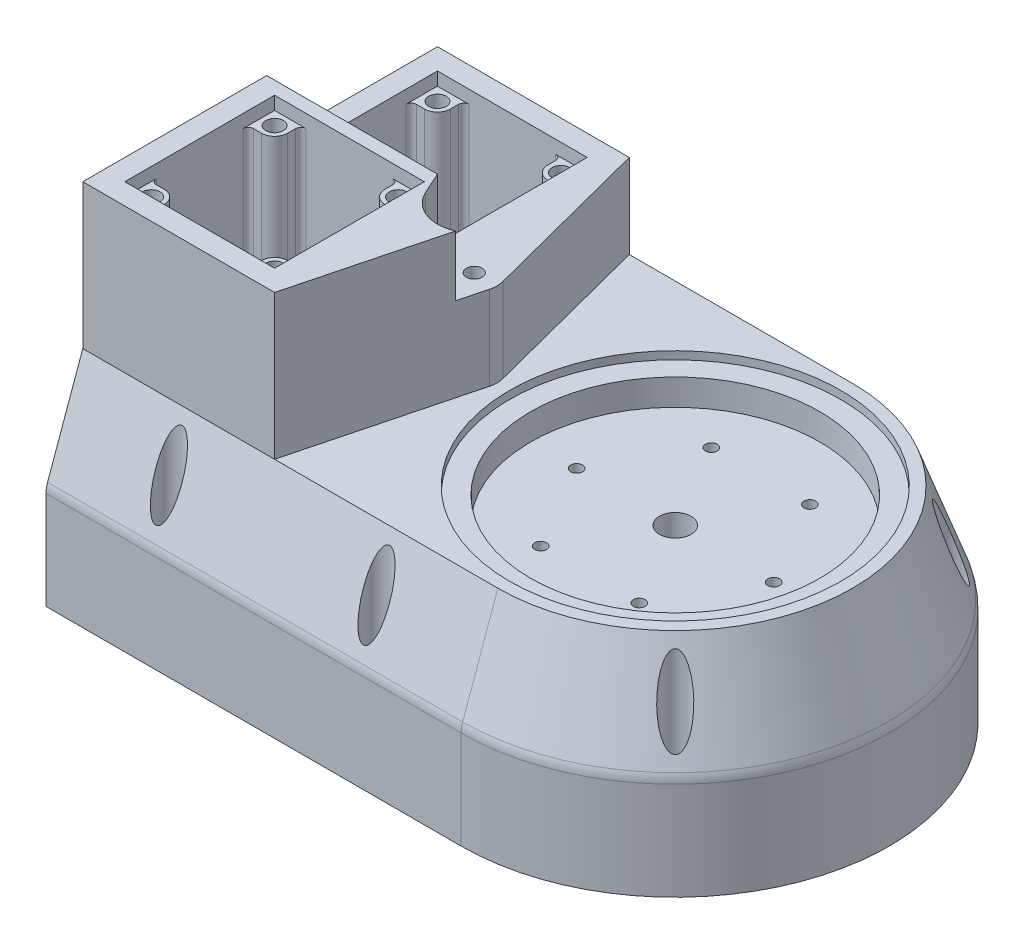
SolidWorks part; units mm, degrees
ref_plane "Alzado" through (0, 0, 0) normal (0, 0, 1) x (1, 0, 0)
ref_plane "Planta" through (0, 0, 0) normal (0, 1, 0) x (1, 0, 0)
ref_plane "Vista lateral" through (0, 0, 0) normal (1, 0, 0) x (0, 0, -1)
sketch "Croquis1" plane through (0, 0, 0) normal (0, 1, 0) x (1, 0, 0)
  line L0 (-55, 0) -> (55, 0) construction
  line L1 (-158, 67.5) -> (0, 67.5)
  line L2 (-158, 67.5) -> (-158, -67.5)
  line L3 (-158, -67.5) -> (0, -67.5)
  line L5 (-158, 67.5) -> (0, -67.5) construction
  line L6 (-158, -67.5) -> (0, 67.5) construction
  line L8 (-58.5, 0) -> (-48.5, 0) construction
  line L9 (-58.5, 0) -> (-48.5, 0) construction
  line L10 (-150, 59.5) -> (-93, 59.5) construction
  line L11 (-150, 59.5) -> (-150, 2.5) construction
  line L12 (-150, 2.5) -> (-93, 2.5) construction
  line L13 (-93, 59.5) -> (-93, 2.5) construction
  arc A0 (0, -67.5) -> (0, 67.5) centre (0, 0) ccw
  circle A1 centre (0, 0) radius 48.5 construction
  circle A2 centre (-71, 0) radius 12.5 construction
  point P4 (-79, 0)
  dimension "D1" = 135
  dimension "D2" = 97
  dimension "D3" = 25
  dimension "D4" = 10
  dimension "D5" = 8
  dimension "D6" = 57
  dimension "D7" = 8
  dimension "D8" = 158
extrude "Saliente-Extruir1" add sketch "Croquis1" along normal blind 110
sketch "Croquis2" plane through (0, 110, 0) normal (0, 1, 0) x (1, 0, 0)
  line L0 (-158, 67.5) -> (-158, -67.5) construction
  line L1 (-140, 59.5) -> (-103, 59.5)
  line L2 (-150, 49.5) -> (-150, 12.5)
  line L3 (-150, 12.5) -> (-140, 12.5)
  line L4 (-93, 49.5) -> (-93, 12.5)
  line L5 (0, 67.5) -> (-158, 67.5) construction
  line L6 (-150, 49.5) -> (-140, 49.5)
  line L7 (-140, 49.5) -> (-140, 59.5)
  line L8 (-121.5, 59.5) -> (-121.5, 2.5) construction
  line L9 (-150, 31) -> (-93, 31) construction
  line L10 (-103, 49.5) -> (-103, 59.5)
  line L11 (-93, 49.5) -> (-103, 49.5)
  line L12 (-93, 12.5) -> (-103, 12.5)
  line L13 (-103, 12.5) -> (-103, 2.5)
  line L14 (-140, 12.5) -> (-140, 2.5)
  line L16 (-140, 2.5) -> (-103, 2.5)
  point P13 (-121.5, 31)
  dimension "D1" = 8
  dimension "D2" = 8
  dimension "D3" = 37
  dimension "D4" = 37
  dimension "D5" = 57
extrude "Cortar-Extruir1" cut sketch "Croquis2" against normal blind 102
fillet "Redondeo1" radius 2 8 edges at (-150, 59, -49.5) (-150, 59, -12.5) (-140, 59, -2.5) (-103, 59, -2.5) (-93, 59, -12.5) (-93, 59, -49.5) (-103, 59, -59.5) (-140, 59, -59.5)
fillet "Redondeo2" radius 5 4 edges at (-103, 59, -12.5) (-140, 59, -12.5) (-103, 59, -49.5) (-140, 59, -49.5)
sketch "Croquis3" plane through (0, 110, 0) normal (0, 1, 0) x (1, 0, 0)
  line L0 (-150, 47.5) -> (-150, 14.5) construction
  line L1 (-150, 2.5) -> (-93, 2.5)
  line L2 (-150, 2.5) -> (-150, 59.5)
  line L3 (-150, 59.5) -> (-93, 59.5)
  line L4 (-93, 2.5) -> (-93, 59.5)
  line L5 (-138, 2.5) -> (-105, 2.5) construction
  line L6 (-105, 59.5) -> (-138, 59.5) construction
  line L7 (-93, 14.5) -> (-93, 47.5) construction
extrude "Cortar-Extruir2" cut sketch "Croquis3" against normal blind 5
sketch "Croquis4" plane through (0, 110, 0) normal (0, 1, 0) x (1, 0, 0)
  circle A0 centre (0, 0) radius 6
  dimension "D1" = 12
extrude "Cortar-Extruir3" cut sketch "Croquis4" against normal blind 100
sketch "Croquis5" plane through (0, 110, 0) normal (0, 1, 0) x (1, 0, 0)
  line L0 (-60.5, 0) -> (60.5, 0) construction
  line L1 (-89, -1000) -> (-89, 49000) construction
  line L2 (-93, 14.5) -> (-93, 47.5) construction
  circle A1 centre (-76.5, 0) radius 12.5 construction
  circle A2 centre (-76.5, 0) radius 3
  circle A3 centre (0, 0) radius 62 construction
  dimension "D1" = 124
  dimension "D2" = 25
  dimension "D4" = 6
  dimension "D3" = 4
extrude "Cortar-Extruir4" cut sketch "Croquis5" against normal blind 100
sketch "Croquis6" plane through (0, 110, 0) normal (0, 1, 0) x (1, 0, 0)
  line L0 (-68.1506, 2.5096) -> (-85, 67.5)
  line L1 (0, 67.5) -> (-158, 67.5) construction
  line L2 (-85, 67.5) -> (0, 67.5)
  line L3 (-60.5, 0) -> (60.5, 0) construction
  line L4 (-85, -67.5) -> (0, -67.5)
  line L5 (-68.1506, -2.5096) -> (-85, -67.5)
  line L6 (-93, 2.5) -> (-93, 59.5) construction
  arc A0 (0, -67.5) -> (0, 67.5) centre (0, 0) ccw
  arc A1 (0, -67.5) -> (0, 67.5) centre (0, 0) ccw construction
  arc A2 (-68.1506, 2.5096) -> (-68.1506, -2.5096) centre (-77.8306, 0) cw
  point P20 (-67.5, 0)
  dimension "D2" = 10
  dimension "D1" = 8
extrude "Cortar-Extruir5" cut sketch "Croquis6" against normal blind 32
sketch "Croquis7" plane through (0, 110, 0) normal (0, 1, 0) x (1, 0, 0)
  line L0 (-70.8172, -12.7947) -> (-85, -67.5)
  line L1 (-68.1506, -2.5096) -> (-85, -67.5) construction
  line L2 (-85, -67.5) -> (-158, -67.5)
  line L3 (-93, 2.5) -> (-158, 2.5)
  line L4 (-158, 67.5) -> (-158, -67.5) construction
  line L5 (-158, 2.5) -> (-158, -67.5)
  line L6 (-138, 2.5) -> (-105, 2.5) construction
  line L7 (-93, 2.5) -> (-89.2537, -5.7744)
  arc A0 (-89.2537, -5.7744) -> (-70.8172, -12.7947) centre (-76.5, 0) ccw
  dimension "D1" = 28
extrude "Saliente-Extruir2" add sketch "Croquis7" along normal blind 23
sketch "Croquis8" plane through (0, 133, 0) normal (0, 1, 0) x (1, 0, 0)
  line L0 (-158, 0) -> (-93, 0) construction
  line L1 (-158, 2.5) -> (-158, -67.5) construction
  line L2 (-105, -59.5) -> (-138, -59.5)
  line L3 (-103, -54.5) -> (-103, -57.5)
  line L4 (-95, -49.5) -> (-98, -49.5)
  line L5 (-93, -14.5) -> (-93, -47.5)
  line L6 (-98, -12.5) -> (-95, -12.5)
  line L7 (-103, -4.5) -> (-103, -7.5)
  line L8 (-138, -2.5) -> (-105, -2.5)
  line L9 (-140, -7.5) -> (-140, -4.5)
  line L10 (-148, -12.5) -> (-145, -12.5)
  line L11 (-150, -47.5) -> (-150, -14.5)
  line L12 (-145, -49.5) -> (-148, -49.5)
  line L13 (-140, 57.5) -> (-140, 54.5)
  line L14 (-145, 49.5) -> (-148, 49.5)
  line L15 (-150, 47.5) -> (-150, 14.5)
  line L16 (-148, 12.5) -> (-145, 12.5)
  line L17 (-140, 7.5) -> (-140, 4.5)
  line L18 (-138, 2.5) -> (-105, 2.5)
  line L19 (-103, 4.5) -> (-103, 7.5)
  line L20 (-98, 12.5) -> (-95, 12.5)
  line L21 (-93, 14.5) -> (-93, 47.5)
  line L22 (-95, 49.5) -> (-98, 49.5)
  line L23 (-103, 54.5) -> (-103, 57.5)
  line L24 (-105, 59.5) -> (-138, 59.5)
  line L25 (-140, 57.5) -> (-140, 54.5) construction
  line L26 (-145, 49.5) -> (-148, 49.5) construction
  line L27 (-150, 47.5) -> (-150, 14.5) construction
  line L28 (-148, 12.5) -> (-145, 12.5) construction
  line L29 (-140, 7.5) -> (-140, 4.5) construction
  line L30 (-138, 2.5) -> (-105, 2.5) construction
  line L31 (-103, 4.5) -> (-103, 7.5) construction
  line L32 (-98, 12.5) -> (-95, 12.5) construction
  line L33 (-93, 14.5) -> (-93, 47.5) construction
  line L34 (-95, 49.5) -> (-98, 49.5) construction
  line L35 (-103, 54.5) -> (-103, 57.5) construction
  line L36 (-105, 59.5) -> (-138, 59.5) construction
  line L37 (-140, -57.5) -> (-140, -54.5)
  line L38 (-158, -67.5) -> (-85, -67.5) construction
  arc A0 (-138, -59.5) -> (-140, -57.5) centre (-138, -57.5) cw
  arc A1 (-103, -57.5) -> (-105, -59.5) centre (-105, -57.5) cw
  arc A2 (-103, -54.5) -> (-98, -49.5) centre (-98, -54.5) cw
  arc A3 (-93, -47.5) -> (-95, -49.5) centre (-95, -47.5) cw
  arc A4 (-95, -12.5) -> (-93, -14.5) centre (-95, -14.5) cw
  arc A5 (-98, -12.5) -> (-103, -7.5) centre (-98, -7.5) cw
  arc A6 (-105, -2.5) -> (-103, -4.5) centre (-105, -4.5) cw
  arc A7 (-140, -4.5) -> (-138, -2.5) centre (-138, -4.5) cw
  arc A8 (-140, -7.5) -> (-145, -12.5) centre (-145, -7.5) cw
  arc A9 (-150, -14.5) -> (-148, -12.5) centre (-148, -14.5) cw
  arc A10 (-148, -49.5) -> (-150, -47.5) centre (-148, -47.5) cw
  arc A11 (-145, -49.5) -> (-140, -54.5) centre (-145, -54.5) cw
  arc A12 (-145, 49.5) -> (-140, 54.5) centre (-145, 54.5) ccw
  arc A13 (-148, 49.5) -> (-150, 47.5) centre (-148, 47.5) ccw
  arc A14 (-150, 14.5) -> (-148, 12.5) centre (-148, 14.5) ccw
  arc A15 (-140, 7.5) -> (-145, 12.5) centre (-145, 7.5) ccw
  arc A16 (-140, 4.5) -> (-138, 2.5) centre (-138, 4.5) ccw
  arc A17 (-105, 2.5) -> (-103, 4.5) centre (-105, 4.5) ccw
  arc A18 (-98, 12.5) -> (-103, 7.5) centre (-98, 7.5) ccw
  arc A19 (-95, 12.5) -> (-93, 14.5) centre (-95, 14.5) ccw
  arc A20 (-93, 47.5) -> (-95, 49.5) centre (-95, 47.5) ccw
  arc A21 (-103, 54.5) -> (-98, 49.5) centre (-98, 54.5) ccw
  arc A22 (-103, 57.5) -> (-105, 59.5) centre (-105, 57.5) ccw
  arc A23 (-138, 59.5) -> (-140, 57.5) centre (-138, 57.5) ccw
  arc A24 (-145, 49.5) -> (-140, 54.5) centre (-145, 54.5) ccw construction
  arc A25 (-148, 49.5) -> (-150, 47.5) centre (-148, 47.5) ccw construction
  arc A26 (-150, 14.5) -> (-148, 12.5) centre (-148, 14.5) ccw construction
  arc A27 (-140, 7.5) -> (-145, 12.5) centre (-145, 7.5) ccw construction
  arc A28 (-140, 4.5) -> (-138, 2.5) centre (-138, 4.5) ccw construction
  arc A29 (-105, 2.5) -> (-103, 4.5) centre (-105, 4.5) ccw construction
  arc A30 (-98, 12.5) -> (-103, 7.5) centre (-98, 7.5) ccw construction
  arc A31 (-95, 12.5) -> (-93, 14.5) centre (-95, 14.5) ccw construction
  arc A32 (-93, 47.5) -> (-95, 49.5) centre (-95, 47.5) ccw construction
  arc A33 (-103, 54.5) -> (-98, 49.5) centre (-98, 54.5) ccw construction
  arc A34 (-103, 57.5) -> (-105, 59.5) centre (-105, 57.5) ccw construction
  arc A35 (-138, 59.5) -> (-140, 57.5) centre (-138, 57.5) ccw construction
  dimension "D2" = 8
  dimension "D1" = 0
extrude "Cortar-Extruir6" cut sketch "Croquis8" against normal blind 102
sketch "Croquis10" plane through (0, 133, 0) normal (0, 1, 0) x (1, 0, 0)
  line L0 (-150, -14.5) -> (-150, -47.5) construction
  line L1 (-150, -2.5) -> (-93, -2.5)
  line L2 (-150, -2.5) -> (-150, -59.5)
  line L3 (-150, -59.5) -> (-93, -59.5)
  line L4 (-93, -2.5) -> (-93, -59.5)
  line L5 (-105, -2.5) -> (-138, -2.5) construction
  line L6 (-93, -47.5) -> (-93, -14.5) construction
  line L7 (-138, -59.5) -> (-105, -59.5) construction
extrude "Cortar-Extruir7" cut sketch "Croquis10" against normal blind 5
sketch "Croquis11" plane through (0, 78, 0) normal (0, 1, 0) x (1, 0, 0)
  line L1 (0, 0) -> (-63, 0) construction
  circle A0 centre (0, 0) radius 63
  circle A1 centre (0, 0) radius 45 construction
  dimension "D1" = 126
  dimension "D2" = 90
extrude "Cortar-Extruir8" cut sketch "Croquis11" against normal blind 3 and the other way through all
sketch "Croquis12" plane through (0, 78, 0) normal (0, 1, 0) x (1, 0, 0)
  circle A0 centre (0, 0) radius 55
  dimension "D1" = 110
extrude "Cortar-Extruir9" cut sketch "Croquis12" against normal blind 13
sketch "Croquis13" plane through (0, 65, 0) normal (0, 1, 0) x (1, 0, 0)
  circle A0 centre (0, 0) radius 37.5 construction
  circle A1 centre (-37.5, 0) radius 1.75
  dimension "D1" = 75
  dimension "D2" = 3.5
extrude "Cortar-Extruir10" cut sketch "Croquis13" against normal blind 14
sketch "Croquis14" plane through (0, 65, 0) normal (0, 1, 0) x (1, 0, 0)
  circle A0 centre (-37.5, 0) radius 2.25
  dimension "D1" = 4.5
extrude "Cortar-Extruir11" cut sketch "Croquis14" against normal blind 5
pattern_circular "MatrizC1" count 6 over 360 about axis through (0, 0, 0) along (0, 1, 0) of "Cortar-Extruir11", "Cortar-Extruir10"
sketch "Croquis16" plane through (0, 110, 0) normal (0, 1, 0) x (1, 0, 0)
  circle A0 centre (-98, 7.5) radius 2.75 construction
  circle A1 centre (-145, 7.5) radius 2.75 construction
  circle A2 centre (-98, 54.5) radius 2.75 construction
  circle A3 centre (-145, 54.5) radius 2.75 construction
  circle A4 centre (-98, 7.5) radius 2.75
  circle A5 centre (-145, 7.5) radius 2.75
  circle A6 centre (-98, 54.5) radius 2.75
  circle A7 centre (-145, 54.5) radius 2.75
sketch "Croquis17" plane through (0, 133, 0) normal (0, 1, 0) x (1, 0, 0)
  circle A0 centre (-145, -54.5) radius 2.75 construction
  circle A1 centre (-98, -54.5) radius 2.75 construction
  circle A2 centre (-98, -7.5) radius 2.75 construction
  circle A3 centre (-145, -7.5) radius 2.75 construction
  circle A4 centre (-145, -54.5) radius 2.75
  circle A5 centre (-98, -54.5) radius 2.75
  circle A6 centre (-98, -7.5) radius 2.75
  circle A7 centre (-145, -7.5) radius 2.75
ref_plane "Plano1" through (0, 39, 0) normal (0, -1, 0) x (-1, 0, 0)
extrude "Cortar-Extruir12" cut sketch "Croquis17" against normal blind 30
sketch "Croquis18" plane through (0, 128, 0) normal (0, 1, 0) x (1, 0, 0)
  circle A0 centre (-145, -7.5) radius 3.35
  circle A1 centre (-98, -7.5) radius 3.35
  circle A2 centre (-98, -54.5) radius 3.35
  circle A3 centre (-145, -54.5) radius 3.35
  dimension "D1" = 6.7
extrude "Cortar-Extruir13" cut sketch "Croquis18" against normal blind 5
extrude "Cortar-Extruir14" cut sketch "Croquis16" against normal blind 30
sketch "Croquis19" plane through (0, 105, 0) normal (0, 1, 0) x (1, 0, 0)
  circle A0 centre (-145, 54.5) radius 3.35
  circle A1 centre (-98, 54.5) radius 3.35
  circle A2 centre (-145, 7.5) radius 3.35
  circle A3 centre (-98, 7.5) radius 3.35
  dimension "D1" = 6.7
extrude "Cortar-Extruir15" cut sketch "Croquis19" against normal blind 5
sketch "Croquis20" plane through (0, 0, 0) normal (0, -1, 0) x (1, 0, 0)
  line L0 (0, -67.5) -> (-158, -67.5) construction
  line L1 (-158, 67.5) -> (0, 67.5) construction
  line L2 (0, -67.5) -> (-158, -67.5)
  line L3 (-158, 67.5) -> (0, 67.5)
  arc A0 (0, -67.5) -> (0, 67.5) centre (0, 0) ccw construction
  arc A1 (0, -67.5) -> (0, 67.5) centre (0, 0) ccw
sketch "Croquis21" plane through (-158, 0, 0) normal (1, 0, 0) x (0, 0, -1)
  line L0 (-67.5, 0) -> (67.5, 0) construction
  line L1 (-67.5, 0) -> (-81.5, 0)
  line L2 (-67.5, 0) -> (-67.5, 39)
  line L4 (-81.5, 0) -> (-81.5, 37.2595)
  line L5 (-74.25, 39) -> (74.25, 39) construction
  line L6 (-80.9119, 40.6381) -> (-67.5, 78)
  line L7 (-67.5, 78) -> (-67.5, 39)
  arc A0 (-80.9119, 40.6381) -> (-81.5, 37.2595) centre (-71.5, 37.2595) ccw
  point P12 (-81.5, 39)
  dimension "D2" = 10
  dimension "D1" = 14
sweep "Barrer1" add profiles "Croquis21" path "Croquis20"
sketch "Croquis22" plane through (0, 39, 0) normal (0, -1, 0) x (-1, 0, 0)
  line L0 (0, -74.206) -> (158, -74.206) construction
  line L1 (158, -67.5) -> (158, -80.9119) construction
  line L2 (0, 74.206) -> (158, 74.206) construction
  line L3 (158, 67.5) -> (158, 80.9119) construction
  line L4 (0, 0) -> (158, 0) construction
  line L5 (158, 2.5) -> (158, -67.5) construction
  line L6 (0, 0) -> (-52.4715, 52.4715) construction
  arc A0 (0, 74.206) -> (0, -74.206) centre (0, 0) ccw construction
  circle A1 centre (118.5, 74.206) radius 3
  circle A2 centre (39.5, 74.206) radius 3
  circle A3 centre (-52.4715, 52.4715) radius 3
  circle A4 centre (118.5, -74.206) radius 3
  circle A5 centre (39.5, -74.206) radius 3
  circle A6 centre (-52.4715, -52.4715) radius 3
  dimension "D1" = 79
  dimension "D2" = 39.5
  dimension "D3" = 6
  dimension "D4" = 45
extrude "Cortar-Extruir16" cut sketch "Croquis22" against normal through all both and the other way through all
sketch "Croquis23" plane through (0, 0, 0) normal (0, 1, 0) x (1, 0, 0)
  line L0 (0, 0) -> (-158, 0) construction
  line L1 (-158, 2.5) -> (-158, -67.5) construction
  circle A0 centre (-118.5, 74.206) radius 5
  circle A1 centre (-39.5, 74.206) radius 5
  circle A2 centre (52.4715, 52.4715) radius 5
  circle A3 centre (52.4715, 52.4715) radius 3 construction
  circle A4 centre (52.4715, -52.4715) radius 5
  circle A5 centre (-39.5, -74.206) radius 5
  circle A6 centre (-118.5, -74.206) radius 5
  dimension "D1" = 10
extrude "Cortar-Extruir17" cut sketch "Croquis23" along normal through all from offset 30
